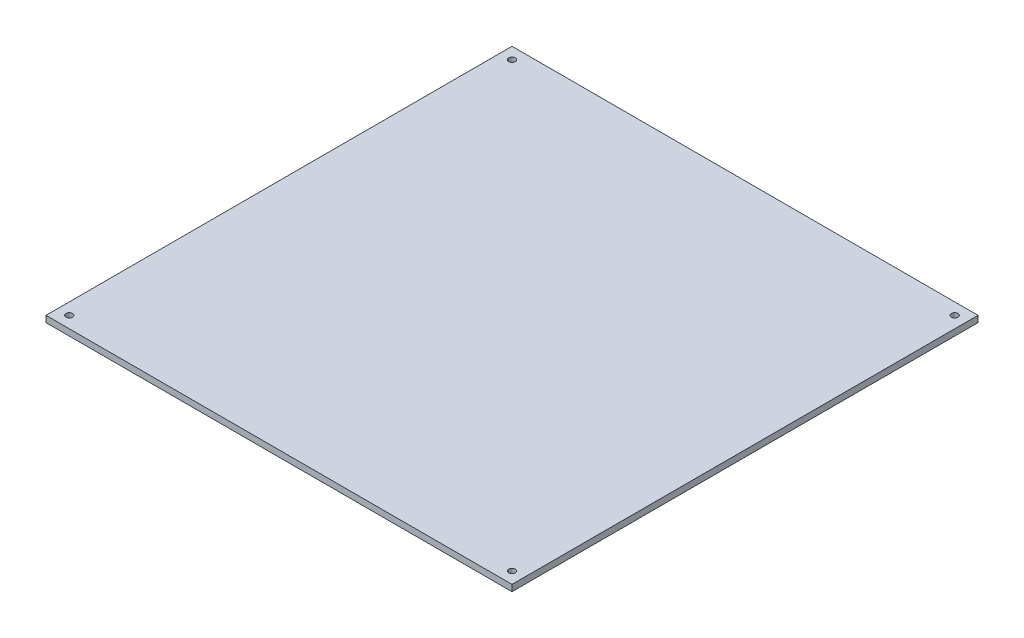
SolidWorks part; units mm, degrees
ref_plane "Front Plane" through (0, 0, 0) normal (0, 0, 1) x (1, 0, 0)
ref_plane "Top Plane" through (0, 0, 0) normal (0, 1, 0) x (1, 0, 0)
ref_plane "Right Plane" through (0, 0, 0) normal (1, 0, 0) x (0, 0, -1)
sketch "Sketch1" plane through (0, 0, 0) normal (0, 1, 0) x (1, 0, 0)
  line L1 (0, 0) -> (220, 0)
  line L2 (0, 0) -> (0, 220)
  line L3 (0, 220) -> (220, 220)
  line L4 (220, 0) -> (220, 220)
  line L5 (5.5, 5.5) -> (214.5, 5.5) construction
  line L6 (5.5, 5.5) -> (5.5, 214.5) construction
  line L7 (5.5, 214.5) -> (214.5, 214.5) construction
  line L8 (214.5, 5.5) -> (214.5, 214.5) construction
  line L9 (5.5, 5.5) -> (214.5, 214.5) construction
  line L10 (5.5, 214.5) -> (214.5, 5.5) construction
  circle A0 centre (5.5, 214.5) radius 1.55
  circle A1 centre (5.5, 5.5) radius 1.55
  circle A2 centre (214.5, 5.5) radius 1.55
  circle A3 centre (214.5, 214.5) radius 1.55
  point P5 (110, 110)
  point P14 (110, 220)
  point P15 (0, 0)
  point P16 (0, 110)
  dimension "D3" = 3.1
  dimension "D4" = 3.1
  dimension "D5" = 3.1
  dimension "D6" = 3.1
  dimension "D1" = 220
  dimension "D2" = 220
  dimension "D7" = 209
  dimension "D8" = 209
extrude "Boss-Extrude1" add sketch "Sketch1" along normal blind 3
